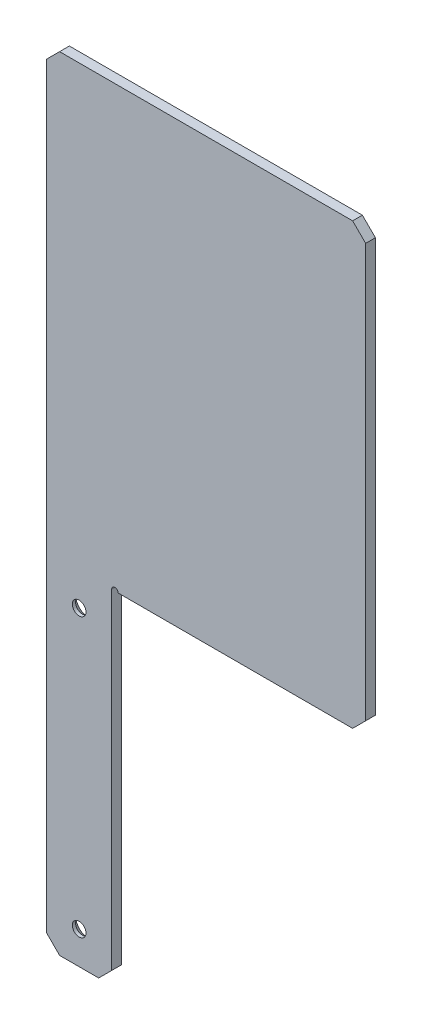
SolidWorks part; units mm, degrees
ref_plane "前视基准面" through (0, 0, 0) normal (0, 0, 1) x (1, 0, 0)
ref_plane "上视基准面" through (0, 0, 0) normal (0, 1, 0) x (1, 0, 0)
ref_plane "右视基准面" through (0, 0, 0) normal (1, 0, 0) x (0, 0, -1)
sketch "草图1" plane through (0, 0, 0) normal (0, 0, 1) x (1, 0, 0)
  line L0 (-49, -120.2) -> (-29, -120.2)
  line L1 (-29, -120.2) -> (-29, -14.8)
  line L2 (-29, -14.8) -> (49, -14.8)
  line L3 (49, -14.8) -> (49, 120.2)
  line L4 (49, 120.2) -> (-49, 120.2)
  line L5 (-49, -14.8) -> (-49, -120.2)
  line L6 (-49, -14.8) -> (-49, 120.2)
  point P7 (0, 120.2)
  dimension "D1" = 20
  dimension "D2" = 105.4
  dimension "D3" = 78
  dimension "D4" = 135
  dimension "D5" = 14.8
extrude "凸台-拉伸1" add sketch "草图1" along normal mid plane 3
chamfer "倒角1" distance 4 angle 45 5 edges at (-49, -120.2, 0) (-29, -120.2, 0) (49, -14.8, 0) (49, 120.2, 0) (-49, 120.2, 0)
sketch "草图2" plane through (0, 0, 1.5) normal (0, 0, 1) x (1, 0, 0)
  line L0 (-29, -14.8) -> (45, -14.8) construction
  circle A0 centre (-28, -14.8) radius 1
  dimension "D1" = 2
extrude "切除-拉伸1" cut sketch "草图2" against normal through all
sketch "草图3" plane through (0, 0, 1.5) normal (0, 0, 1) x (1, 0, 0)
  line L0 (-39, -24.8) -> (-39, -110.2) construction
  line L1 (-45, -120.2) -> (-33, -120.2) construction
  line L2 (-27, -14.8) -> (45, -14.8) construction
  line L3 (-29, -116.2) -> (-29, -14.8) construction
  circle A0 centre (-39, -110.2) radius 2.1
  circle A1 centre (-39, -24.8) radius 2.1
  dimension "D1" = 10
  dimension "D2" = 10
  dimension "D4" = 4.2
  dimension "D3" = 10
extrude "切除-拉伸2" cut sketch "草图3" against normal through all
chamfer "倒角2" distance 2 angle 45 2 edges at (-36.9, -110.2, -1.5) (-36.9, -24.8, -1.5)
